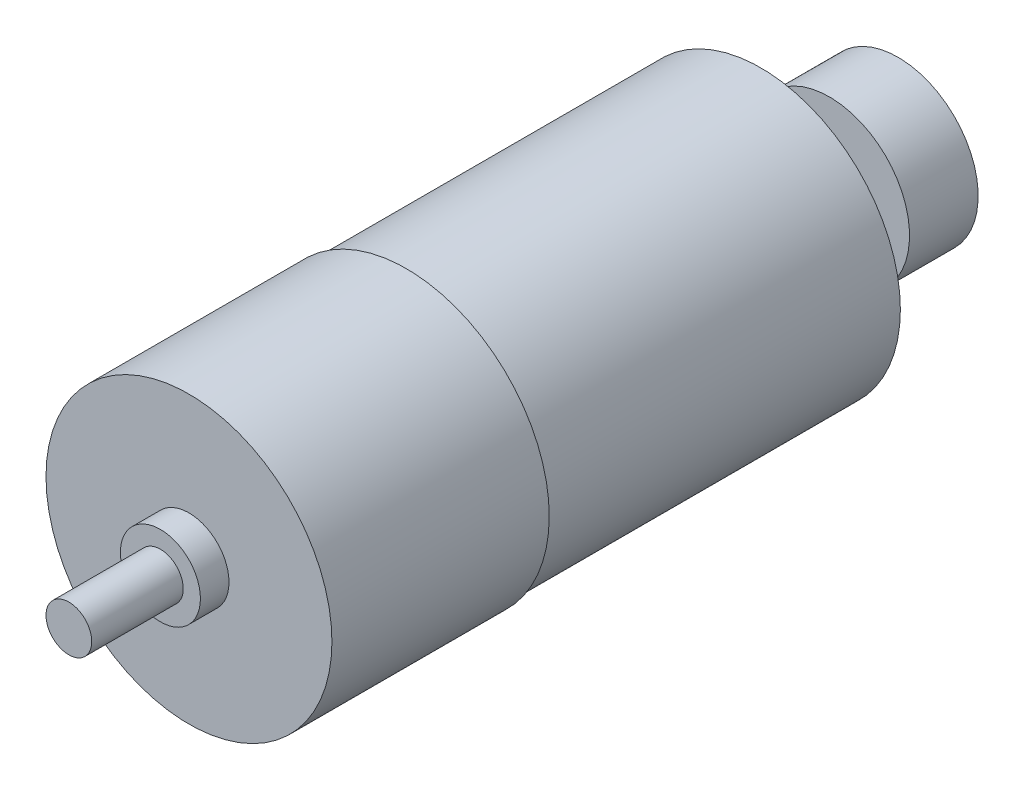
SolidWorks part; units mm, degrees
ref_plane "Alzado" through (0, 0, 0) normal (0, 0, 1) x (1, 0, 0)
ref_plane "Planta" through (0, 0, 0) normal (0, 1, 0) x (1, 0, 0)
ref_plane "Vista lateral" through (0, 0, 0) normal (1, 0, 0) x (0, 0, -1)
sketch "Croquis1" plane through (0, 0, 0) normal (0, 0, 1) x (1, 0, 0)
  circle A0 centre (0, 0) radius 12.5
  dimension "D1" = 25
extrude "Saliente-Extruir1" add sketch "Croquis1" along normal blind 19
sketch "Croquis3" plane through (0, 0, 19) normal (0, 0, 1) x (1, 0, 0)
  circle A0 centre (0, 0) radius 3.5
extrude "Saliente-Extruir2" add sketch "Croquis3" along normal blind 2.5 from surface at 0 starting at face at (12.5, 0, 19)
sketch "Croquis4" plane through (0, 0, 21.5) normal (0, 0, 1) x (1, 0, 0)
  circle A0 centre (0, 0) radius 2
extrude "Saliente-Extruir3" add sketch "Croquis4" along normal blind 8
sketch "Croquis5" plane through (0, 0, 0) normal (0, 0, -1) x (-1, 0, 0)
  circle A0 centre (0, 0) radius 12.2
extrude "Saliente-Extruir4" add sketch "Croquis5" along normal blind 31
sketch "Croquis6" plane through (0, 0, -31) normal (0, 0, -1) x (-1, 0, 0)
  circle A0 centre (0, 0) radius 2
extrude "Saliente-Extruir5" add sketch "Croquis6" along normal blind 6
sketch "Croquis7" plane through (0, 0, -37) normal (0, 0, -1) x (-1, 0, 0)
  circle A0 centre (0, 0) radius 7
extrude "Saliente-Extruir6" add sketch "Croquis7" along normal blind 6
